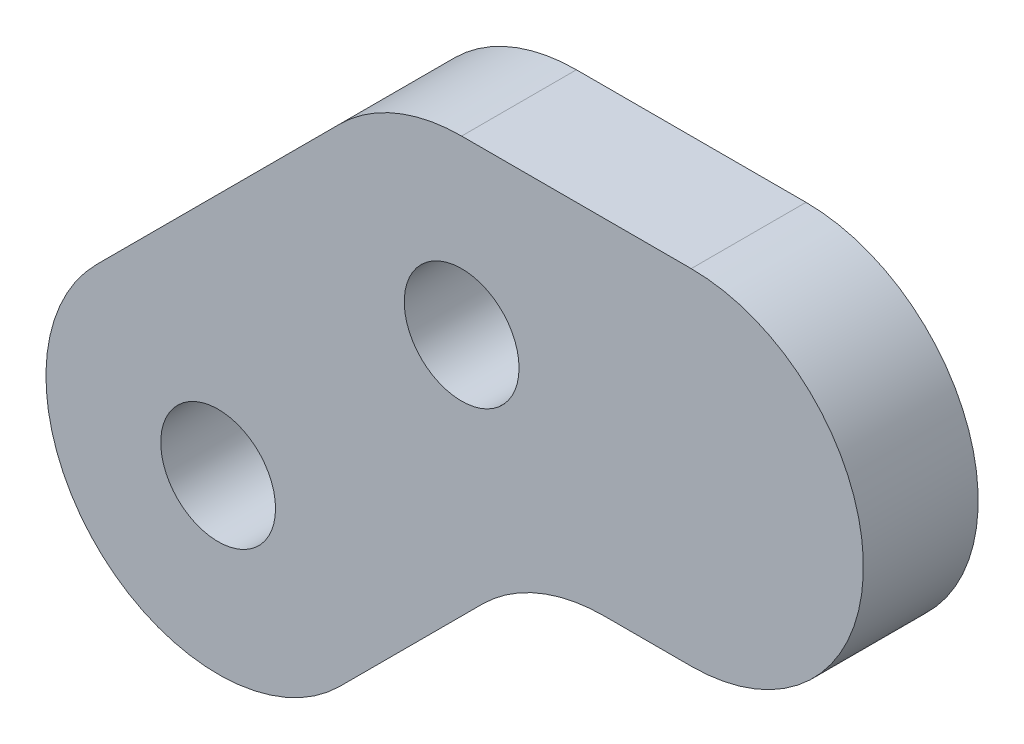
SolidWorks part; units mm, degrees
ref_plane "Alzado" through (0, 0, 0) normal (0, 0, 1) x (1, 0, 0)
ref_plane "Planta" through (0, 0, 0) normal (0, 1, 0) x (1, 0, 0)
ref_plane "Vista lateral" through (0, 0, 0) normal (1, 0, 0) x (0, 0, -1)
sketch "Model" plane through (0, 0, 0) normal (0, 0, 1) x (1, 0, 0)
  line L0 (139.5991, 257.4957) -> (133.5991, 257.4957)
  line L1 (138.0991, 248.4957) -> (139.5991, 248.4957)
  line L2 (124.0532, 249.8137) -> (130.4171, 256.1777)
  line L4 (130.4171, 243.4497) -> (134.1451, 247.1777)
  line L5 (138.0991, 248.4957) -> (137.327, 248.4957)
  arc A0 (139.5991, 248.4957) -> (139.5991, 257.4957) centre (139.5991, 252.9957) ccw
  arc A1 (133.5991, 257.4957) -> (130.4171, 256.1777) centre (133.5991, 252.9957) ccw
  circle A2 centre (133.5991, 252.9957) radius 1.5
  arc A3 (124.0532, 249.8137) -> (130.4171, 243.4497) centre (127.2352, 246.6317) ccw
  circle A4 centre (127.2352, 246.6317) radius 1.5
  arc A5 (137.327, 248.4957) -> (134.1451, 247.1777) centre (137.327, 243.9957) ccw
extrude "Saliente-Extruir1" add sketch "Model" along normal blind 3
